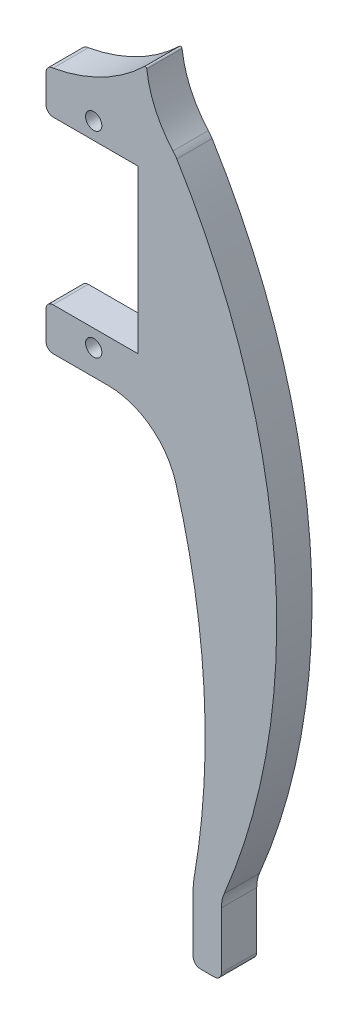
SolidWorks part; units mm, degrees
ref_plane "Front Plane" through (0, 0, 0) normal (0, 0, 1) x (1, 0, 0)
ref_plane "Top Plane" through (0, 0, 0) normal (0, 1, 0) x (1, 0, 0)
ref_plane "Right Plane" through (0, 0, 0) normal (1, 0, 0) x (0, 0, -1)
sketch "Sketch1" plane through (0, 0, 0) normal (0, 0, 1) x (1, 0, 0)
  line L0 (-6.5, 11.5) -> (-6.5, 17.5)
  line L1 (-6.5, 11.5) -> (6.5, 11.5)
  line L3 (-6.5, -11.5) -> (6.5, -11.5)
  line L4 (6.5, 11.5) -> (6.5, -11.5)
  line L5 (-6.5, 11.5) -> (6.5, -11.5) construction
  line L6 (-6.5, -11.5) -> (6.5, 11.5) construction
  line L7 (-6.5, 17.5) -> (9.5, 17.5)
  line L9 (-6.5, -11.5) -> (-6.5, -17.5)
  line L10 (-6.5, -17.5) -> (9.5, -17.5)
  line L11 (9.5, 17.5) -> (9.5, -17.5)
  line L12 (9.5, 17.5) -> (10.5, 17.5)
  line L13 (10.5, 17.5) -> (10.5, -103.8528) construction
  line L16 (9.5, 17.5) -> (10.5, 17.5)
  line L17 (14.3281, -75.0786) -> (14.3281, -82.5)
  line L18 (14.3281, -72.5) -> (14.3281, -75.0786)
  line L19 (14.3281, -82.5) -> (18.3281, -82.5)
  line L20 (18.3281, -75.0786) -> (18.3281, -72.5)
  line L22 (18.3281, -75.0786) -> (18.3281, -82.5)
  arc A0 (10.5, 17.5) -> (18.3281, -72.5) centre (-68.846, -34.7419) cw
  arc A1 (9.5, -17.5) -> (14.3281, -72.5) centre (-88.0018, -53.771) cw
  point P0 (0, 0)
  dimension "D11" = 4
  dimension "D12" = 104.0298
  dimension "D13" = 4
  dimension "D15" = 7.4214
  dimension "D16" = 7.6563
  dimension "D17" = 10
  dimension "D10" = 95
  dimension "D1" = 23
  dimension "D2" = 13
  dimension "D3" = 6
  dimension "D4" = 16
  dimension "D5" = 16
  dimension "D6" = 6
  dimension "D7" = 13
  dimension "D8" = 100
  dimension "D9" = 1
  dimension "D14" = 7.4214
extrude "Boss-Extrude1" add sketch "Sketch1" along normal blind 5
sketch "Sketch2" plane through (0, 0, 5) normal (0, 0, 1) x (1, 0, 0)
  line L0 (6.5, 11.5) -> (6.5, -11.5) construction
  line L1 (-6.5, 11.5) -> (6.5, 11.5) construction
  line L2 (-6.5, -11.5) -> (6.5, -11.5) construction
  circle A0 centre (0.25, 13.9) radius 1.15
  circle A1 centre (0.25, -13.9) radius 1.15
  dimension "D1" = 2.3
  dimension "D4" = 6.25
  dimension "D6" = 2.3
  dimension "D2" = 6.25
  dimension "D3" = 2.4
  dimension "D5" = 2.4
extrude "Cut-Extrude1" cut sketch "Sketch2" against normal through all
fillet "Fillet1" radius 5 1 edges at (10.5, 17.5, 2.5)
fillet "Fillet3" radius 1 4 edges at (-6.5, -17.5, 2.5) (-6.5, -11.5, 2.5) (-6.5, 11.5, 2.5) (-6.5, 17.5, 2.5)
fillet "Fillet12" radius 5 1 edges at (18.3281, -72.5, 2.5)
fillet "Fillet14" radius 1 2 edges at (18.3281, -82.5, 2.5) (14.3281, -82.5, 2.5)
fillet "Fillet15" radius 10 1 edges at (14.3281, -72.5, 2.5)
fillet "Fillet16" radius 10 1 edges at (9.5, -17.5, 2.5)
sketch "Sketch3" plane through (0, 0, 5) normal (0, 0, 1) x (1, 0, 0)
  line L0 (-5.5, 17.5) -> (7.7582, 17.5)
  line L1 (7.7582, 17.5) -> (7.7582, 24.5)
  arc A0 (-5.5, 17.5) -> (7.7582, 24.5) centre (-10.0062, 42.0905) ccw
  dimension "D1" = 25
  dimension "D2" = 7
extrude "Boss-Extrude2" add sketch "Sketch3" against normal blind 5
fillet "Fillet17" radius 0.2 1 edges at (7.7582, 24.5, 2.5)
fillet "Fillet18" radius 15 1 edges at (7.7582, 17.5, 2.5)
